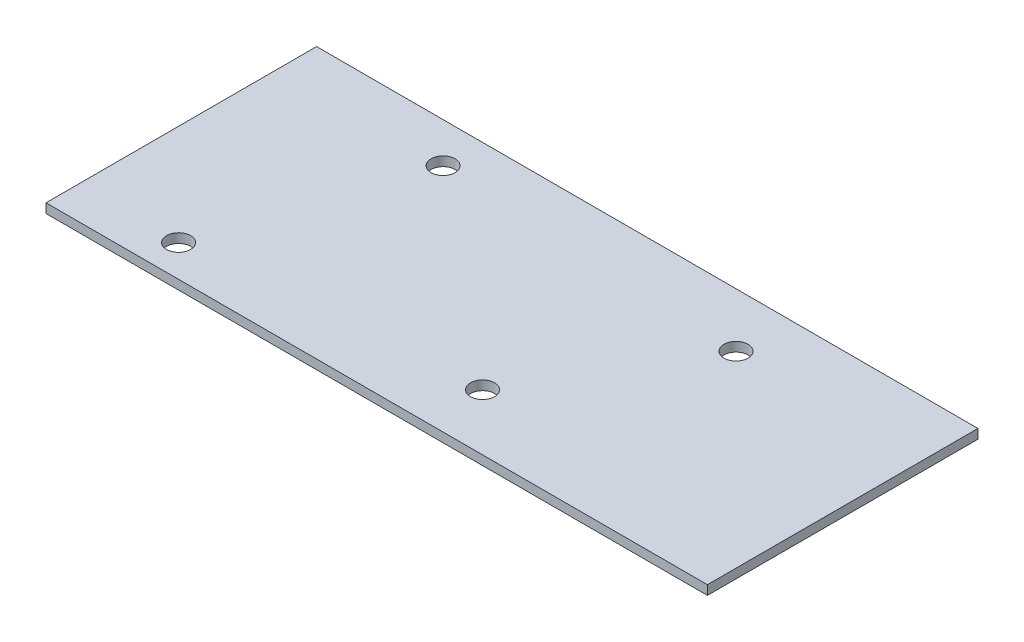
SolidWorks part; units mm, degrees
ref_plane "Plan de face" through (0, 0, 0) normal (0, 0, 1) x (1, 0, 0)
ref_plane "Plan de dessus" through (0, 0, 0) normal (0, 1, 0) x (1, 0, 0)
ref_plane "Plan de droite" through (0, 0, 0) normal (1, 0, 0) x (0, 0, -1)
sketch "Esquisse1" plane through (0, 0, 0) normal (0, 1, 0) x (1, 0, 0)
  line L0 (-55, 22.5) -> (55, -22.5) construction
  line L1 (-55, 22.5) -> (55, 22.5)
  line L2 (-55, 22.5) -> (-55, -22.5)
  line L3 (-55, -22.5) -> (55, -22.5)
  line L4 (55, 22.5) -> (55, -22.5)
  line L5 (55, -22.5) -> (55.2925, -21.6226) construction
  dimension "D1" = 110
  dimension "D2" = 45
extrude "Boss.-Extru.1" add sketch "Esquisse1" along normal blind 1.55
sketch "Esquisse2" plane through (0, 1.55, 0) normal (0, 1, 0) x (1, 0, 0)
  line L0 (-55, -22.5) -> (55, -22.5) construction
  line L1 (-55, 22.5) -> (-55, -22.5) construction
  circle A0 centre (-38.25, -17.2) radius 2
  circle A1 centre (-27.32, 15.86) radius 2
  circle A2 centre (23.75, 13.5) radius 2
  circle A3 centre (8.23, -13.12) radius 2
  dimension "D1" = 4
  dimension "D2" = 4
  dimension "D3" = 4
  dimension "D4" = 4
  dimension "D5" = 5.3
  dimension "D6" = 16.75
  dimension "D7" = 38.36
  dimension "D8" = 27.68
  dimension "D9" = 36
  dimension "D10" = 78.75
  dimension "D11" = 63.23
  dimension "D12" = 9.38
extrude "Enlèv. mat.-Extru.1" cut sketch "Esquisse2" against normal blind 3
